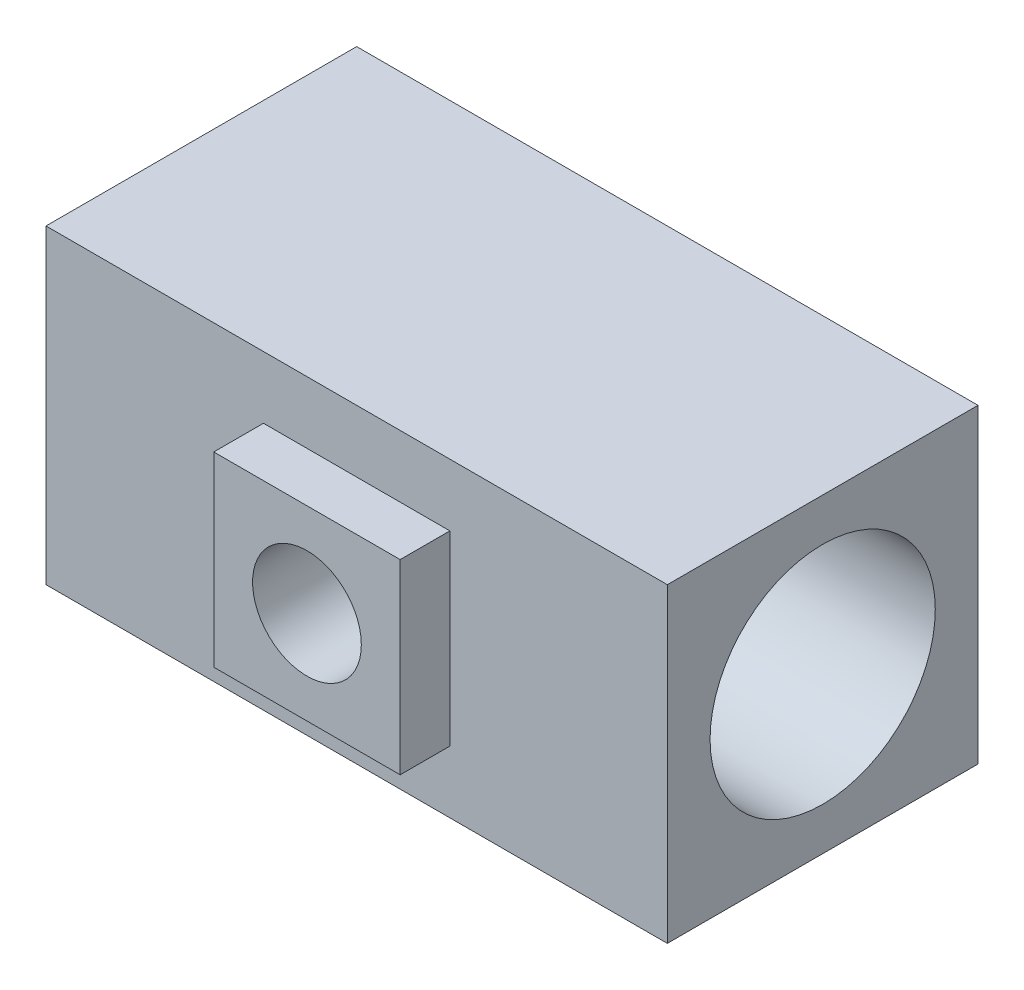
SolidWorks part; units mm, degrees
material "6061 Alloy"
ref_plane "X-Y Datum" through (0, 0, 0) normal (0, 0, 1) x (1, 0, 0)
ref_plane "X-Z Datum" through (0, 0, 0) normal (0, 1, 0) x (1, 0, 0)
ref_plane "Y-Z Datum" through (0, 0, 0) normal (1, 0, 0) x (0, 0, -1)
sketch "Sketch2" plane through (0, 0, 0) normal (0, 1, 0) x (1, 0, 0)
  line L1 (-31.75, -15.875) -> (31.75, -15.875)
  line L2 (-31.75, -15.875) -> (-31.75, 15.875)
  line L3 (-31.75, 15.875) -> (31.75, 15.875)
  line L4 (31.75, -15.875) -> (31.75, 15.875)
  line L5 (-31.75, -15.875) -> (31.75, 15.875) construction
  line L6 (-31.75, 15.875) -> (31.75, -15.875) construction
  point P0 (0, 0)
  dimension "D1" = 31.75
  dimension "D2" = 63.5
extrude "Boss-Extrude1" add sketch "Sketch2" along normal blind 31.75
hole_wizard "29/32 (0.90625) Diameter Hole1" positions "Sketch7" profile "Sketch6" hole size "29/32" standard "ANSI Inch" end condition through all
sketch "Sketch7" plane through (31.75, 0, 0) normal (1, 0, 0) x (0, 0, -1)
  line L0 (-15.875, 31.75) -> (15.875, 0)
  point P0 (0, 15.875)
sketch "Sketch6" plane through (31.75, 15.875, 0) normal (0, 1, 0) x (0, 0, -1)
  line L0 (0, 0) -> (0, 63.5)
  line L1 (0, 63.5) -> (11.5094, 63.5)
  line L2 (11.5094, 63.5) -> (11.5094, 0)
  line L5 (11.5094, 0) -> (0, 0)
  line L11 (0, -6.35) -> (0, 107.95) construction
  dimension "Thru Hole Dia." = 23.0187
  dimension "Thru Hole Depth" = 63.5
sketch "Sketch10" plane through (0, 0, 15.875) normal (0, 0, 1) x (1, 0, 0)
  line L0 (-31.75, 31.75) -> (31.75, 0)
  line L2 (-9.525, 6.35) -> (9.525, 6.35)
  line L3 (-9.525, 6.35) -> (-9.525, 25.4)
  line L4 (-9.525, 25.4) -> (9.525, 25.4)
  line L5 (9.525, 6.35) -> (9.525, 25.4)
  line L6 (-9.525, 6.35) -> (9.525, 25.4) construction
  line L7 (-9.525, 25.4) -> (9.525, 6.35) construction
  point P4 (0, 15.875)
  dimension "D1" = 19.05
  dimension "D2" = 19.05
extrude "Boss-Extrude2" add sketch "Sketch10" along normal blind 5.08 contours L2 L5 L0 L3 | L0 L5 L4 L3
hole_wizard "7/16 (0.4375) Diameter Hole1" positions "Sketch11" profile "Sketch12" hole size "7/16" standard "ANSI Inch"
sketch "Sketch11" plane through (0, 0, 20.955) normal (0, 0, 1) x (1, 0, 0)
  line L0 (-9.525, 25.4) -> (9.525, 6.35)
  point P0 (0, 15.875)
sketch "Sketch12" plane through (0, 15.875, 20.955) normal (1, 0, 0) x (0, -1, 0)
  line L0 (0, 0) -> (0, 28.7385)
  line L1 (0, 28.7385) -> (5.5562, 25.4)
  line L2 (5.5562, 25.4) -> (5.5562, 0)
  line L5 (5.5562, 0) -> (0, 0)
  line L10 (0, 28.7385) -> (-5.5563, 25.4) construction
  line L11 (0, -6.35) -> (0, 107.95) construction
  dimension "Hole Dia." = 11.1125
  dimension "Hole Depth" = 25.4
  dimension "Drill Angle" = 118
thread "Thread1" [suppressed] pitch 1.8143 start angle 0, offset 0, length 15.875, pitch 1.8143, diameter 23.4158
ref_plane "Plane1" through (31.75, 15.875, 11.7079) normal (0, -1, 0) x (0, 0, 1)
sketch "Thread Profile1" plane through (31.75, 15.875, 11.7079) normal (0, -1, 0) x (0, 0, 1)
  line L0 (0, 0) -> (0, 1.8143) construction
  line L1 (0, 0) -> (0.982, 0.567)
  line L2 (0.982, 0.567) -> (0.982, 0.7937)
  line L3 (0.982, 0.7937) -> (0, 1.3607)
  line L4 (0.982, 0.6804) -> (0, 0.6804) construction
  line L11 (0, 0) -> (0, 1.3607)
  point P2 (0, 0)
  dimension "Pitch" = 1.8143
  dimension "Profile_Angle" = 60
  dimension "Profile_Land" = 0.2268
  dimension "Profile_Height" = 0.982
thread "Thread2" [suppressed] pitch 1.8143 start angle 0, offset 0, length 15.875, pitch 1.8143, diameter 23.4158
ref_plane "Plane2" through (-31.75, 15.875, -11.7079) normal (0, -1, 0) x (0, 0, -1)
sketch "Thread Profile2" plane through (-31.75, 15.875, -11.7079) normal (0, -1, 0) x (0, 0, -1)
  line L0 (0, 0) -> (0, 1.8143) construction
  line L1 (0, 0) -> (0.982, 0.567)
  line L2 (0.982, 0.567) -> (0.982, 0.7937)
  line L3 (0.982, 0.7937) -> (0, 1.3607)
  line L4 (0.982, 0.6804) -> (0, 0.6804) construction
  line L11 (0, 0) -> (0, 1.3607)
  point P2 (0, 0)
  dimension "Pitch" = 1.8143
  dimension "Profile_Angle" = 60
  dimension "Profile_Land" = 0.2268
  dimension "Profile_Height" = 0.982
thread "Thread4" [suppressed] pitch 1.8143 start angle 0, offset 0, length 0, pitch 1.8143, diameter 11.1125
ref_plane "Plane4" through (-5.5562, 15.875, 20.955) normal (0, -1, 0) x (-1, 0, 0)
sketch "Thread Profile4" plane through (-5.5562, 15.875, 20.955) normal (0, -1, 0) x (-1, 0, 0)
  line L0 (0, 0) -> (0, 1.8143) construction
  line L1 (0, 0) -> (0.982, 0.567)
  line L2 (0.982, 0.567) -> (0.982, 0.7937)
  line L3 (0.982, 0.7937) -> (0, 1.3607)
  line L4 (0.982, 0.6804) -> (0, 0.6804) construction
  line L11 (0, 0) -> (0, 1.3607)
  point P2 (0, 0)
  dimension "Pitch" = 1.8143
  dimension "Profile_Angle" = 60
  dimension "Profile_Land" = 0.2268
  dimension "Profile_Height" = 0.982
sketch "Sketch13" plane through (-31.75, 0, 0) normal (-1, 0, 0) x (0, 0, 1)
  line L4 (-15.875, 0) -> (15.875, 0)
  line L5 (15.875, 0) -> (15.875, 31.75)
  line L6 (15.875, 31.75) -> (-15.875, 31.75)
  line L7 (-15.875, 31.75) -> (-15.875, 0)
  line L8 (-15.875, 0) -> (15.875, 0)
  line L9 (15.875, 0) -> (15.875, 31.75)
  line L10 (15.875, 31.75) -> (-15.875, 31.75)
  line L11 (-15.875, 31.75) -> (-15.875, 0)
  circle A0 centre (0, 15.875) radius 11.5094 construction
  circle A1 centre (0, 15.875) radius 11.5094 construction
  circle A2 centre (0, 15.875) radius 15.3194
  dimension "D1" = 3.81
  dimension "D2" = 0
extrude "Cut-Extrude1" [suppressed] cut sketch "Sketch13" against normal up to surface (22.225 mm away)
sketch "Sketch14" [suppressed] plane through (31.75, 0, 0) normal (1, 0, 0) x (0, 0, -1)
  line L4 (-15.875, 0) -> (15.875, 0)
  line L5 (15.875, 0) -> (15.875, 31.75)
  line L6 (15.875, 31.75) -> (-15.875, 31.75)
  line L7 (-15.875, 31.75) -> (-15.875, 0)
  line L8 (-15.875, 0) -> (15.875, 0)
  line L9 (15.875, 0) -> (15.875, 31.75)
  line L10 (15.875, 31.75) -> (-15.875, 31.75)
  line L11 (-15.875, 31.75) -> (-15.875, 0)
  circle A2 centre (0, 15.875) radius 15.5179
  circle A3 centre (0, 15.875) radius 15.5179
  dimension "D1" = 0
  dimension "D2" = 3.81
extrude "Cut-Extrude2" [suppressed] cut sketch "Sketch14" against normal up to surface (22.225 mm away)
